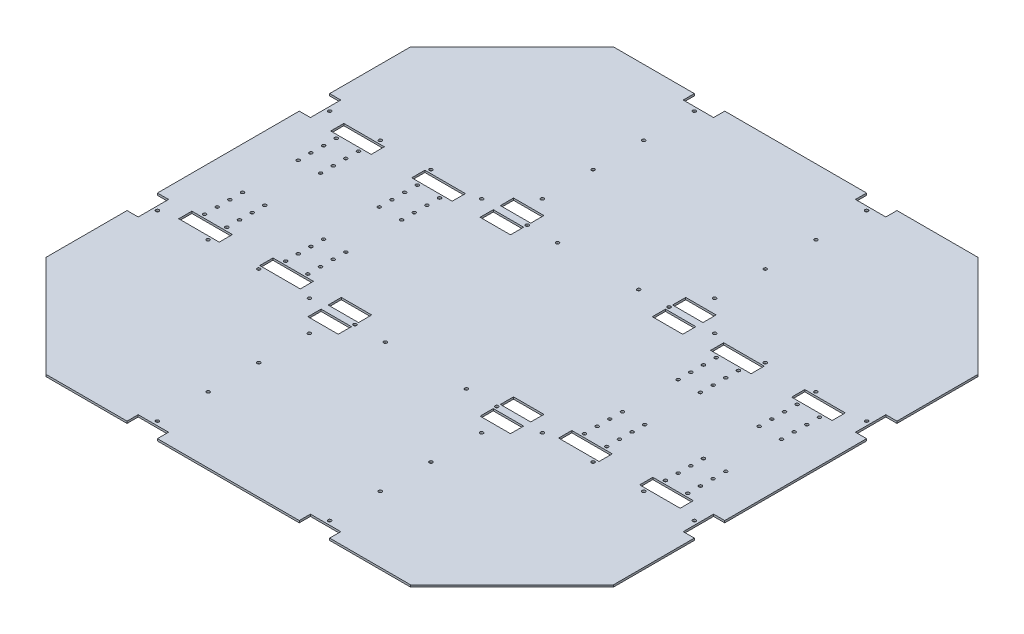
SolidWorks part; units mm, degrees
material "环氧树脂"
ref_plane "前视基准面" through (0, 0, 0) normal (0, 0, 1) x (1, 0, 0)
ref_plane "上视基准面" through (0, 0, 0) normal (0, 1, 0) x (1, 0, 0)
ref_plane "右视基准面" through (0, 0, 0) normal (1, 0, 0) x (0, 0, -1)
sketch "草图1" plane through (0, 0, 0) normal (0, 1, 0) x (1, 0, 0)
  line L0 (0, 365.534) -> (0, -389.8058) construction
  line L1 (-390.2913, 0) -> (444.6602, 0) construction
  line L3 (-280, 280) -> (280, 280)
  line L4 (-280, 280) -> (-280, -280)
  line L5 (-280, -280) -> (280, -280)
  line L6 (280, 280) -> (280, -280)
  line L7 (-280, 280) -> (280, -280) construction
  line L8 (-280, -280) -> (280, 280) construction
  point P5 (0, 0)
  point P10 (0, -389.8058)
  dimension "D1" = 560
extrude "凸台-拉伸1" add sketch "草图1" along normal blind 2
sketch "草图3" plane through (0, 2, 0) normal (0, 1, 0) x (1, 0, 0)
  line L0 (0, 280) -> (0, -280) construction
  line L1 (280, 280) -> (-280, 280) construction
  line L2 (-280, -280) -> (280, -280) construction
  circle A0 centre (265, 85) radius 1.6 construction
  circle A1 centre (265, 85) radius 1.6
  circle A2 centre (215, 85) radius 1.6 construction
  circle A3 centre (215, 85) radius 1.6
  circle A4 centre (165, 85) radius 1.6 construction
  circle A5 centre (165, 85) radius 1.6
  circle A6 centre (115, 85) radius 1.6 construction
  circle A7 centre (115, 85) radius 1.6
  circle A8 centre (85, 265) radius 1.6 construction
  circle A9 centre (85, 265) radius 1.6
  circle A10 centre (85, 215) radius 1.6 construction
  circle A11 centre (85, 215) radius 1.6
  circle A12 centre (85, 165) radius 1.6 construction
  circle A13 centre (85, 165) radius 1.6
  circle A14 centre (85, 115) radius 1.6 construction
  circle A15 centre (85, 115) radius 1.6
  circle A16 centre (-85, 265) radius 1.6 construction
  circle A17 centre (-85, 265) radius 1.6
  circle A18 centre (-85, 215) radius 1.6 construction
  circle A19 centre (-85, 215) radius 1.6
  circle A20 centre (-85, 165) radius 1.6 construction
  circle A21 centre (-85, 165) radius 1.6
  circle A22 centre (-85, 115) radius 1.6 construction
  circle A23 centre (-85, 115) radius 1.6
  circle A24 centre (-115, 85) radius 1.6 construction
  circle A25 centre (-115, 85) radius 1.6
  circle A26 centre (-165, 85) radius 1.6 construction
  circle A27 centre (-165, 85) radius 1.6
  circle A28 centre (-215, 85) radius 1.6 construction
  circle A29 centre (-215, 85) radius 1.6
  circle A30 centre (-265, 85) radius 1.6 construction
  circle A31 centre (-265, 85) radius 1.6
  circle A32 centre (70, 85) radius 1.6 construction
  circle A33 centre (70, 85) radius 1.6
  circle A34 centre (40, 85) radius 1.6 construction
  circle A35 centre (40, 85) radius 1.6
  circle A36 centre (-40, 85) radius 1.6 construction
  circle A37 centre (-40, 85) radius 1.6
  circle A38 centre (-70, 85) radius 1.6 construction
  circle A39 centre (-70, 85) radius 1.6
  circle A40 centre (70, -85) radius 1.6 construction
  circle A41 centre (70, -85) radius 1.6
  circle A42 centre (40, -85) radius 1.6 construction
  circle A43 centre (40, -85) radius 1.6
  circle A44 centre (-40, -85) radius 1.6 construction
  circle A45 centre (-40, -85) radius 1.6
  circle A46 centre (-70, -85) radius 1.6 construction
  circle A47 centre (-70, -85) radius 1.6
  circle A48 centre (-115, -85) radius 1.6 construction
  circle A49 centre (-115, -85) radius 1.6
  circle A50 centre (-165, -85) radius 1.6 construction
  circle A51 centre (-165, -85) radius 1.6
  circle A52 centre (-215, -85) radius 1.6 construction
  circle A53 centre (-215, -85) radius 1.6
  circle A54 centre (-265, -85) radius 1.6 construction
  circle A55 centre (-265, -85) radius 1.6
  circle A56 centre (115, -85) radius 1.6 construction
  circle A57 centre (115, -85) radius 1.6
  circle A58 centre (165, -85) radius 1.6 construction
  circle A59 centre (165, -85) radius 1.6
  circle A60 centre (215, -85) radius 1.6 construction
  circle A61 centre (215, -85) radius 1.6
  circle A62 centre (265, -85) radius 1.6 construction
  circle A63 centre (265, -85) radius 1.6
  circle A66 centre (85, -165) radius 1.6 construction
  circle A67 centre (85, -165) radius 1.6
  circle A68 centre (85, -215) radius 1.6 construction
  circle A69 centre (85, -215) radius 1.6
  circle A70 centre (85, -265) radius 1.6 construction
  circle A71 centre (85, -265) radius 1.6
  circle A72 centre (85, -115) radius 1.6 construction
  circle A73 centre (85, -115) radius 1.6
  circle A74 centre (-85, -115) radius 1.6 construction
  circle A75 centre (-85, -115) radius 1.6
  circle A76 centre (-85, -165) radius 1.6 construction
  circle A77 centre (-85, -165) radius 1.6
  circle A78 centre (-85, -215) radius 1.6 construction
  circle A79 centre (-85, -215) radius 1.6
  circle A80 centre (-85, -265) radius 1.6 construction
  circle A81 centre (-85, -265) radius 1.6
  circle A82 centre (136.5, 65) radius 1.6 construction
  circle A83 centre (136.5, 65) radius 1.6
  circle A84 centre (136.5, 52.5) radius 1.6 construction
  circle A85 centre (136.5, 52.5) radius 1.6
  circle A86 centre (136.5, 40) radius 1.6 construction
  circle A87 centre (136.5, 40) radius 1.6
  circle A88 centre (136.5, 27.5) radius 1.6 construction
  circle A89 centre (136.5, 27.5) radius 1.6
  circle A90 centre (136.5, -40) radius 1.6 construction
  circle A91 centre (136.5, -40) radius 1.6
  circle A92 centre (136.5, -27.5) radius 1.6 construction
  circle A93 centre (136.5, -27.5) radius 1.6
  circle A94 centre (136.5, -52.5) radius 1.6 construction
  circle A95 centre (136.5, -52.5) radius 1.6
  circle A96 centre (136.5, -65) radius 1.6 construction
  circle A97 centre (136.5, -65) radius 1.6
  circle A98 centre (158.5, -65) radius 1.6 construction
  circle A99 centre (158.5, -65) radius 1.6
  circle A100 centre (158.5, -52.5) radius 1.6 construction
  circle A101 centre (158.5, -52.5) radius 1.6
  circle A102 centre (158.5, -40) radius 1.6 construction
  circle A103 centre (158.5, -40) radius 1.6
  circle A104 centre (158.5, -27.5) radius 1.6 construction
  circle A105 centre (158.5, -27.5) radius 1.6
  circle A106 centre (158.5, 27.5) radius 1.6 construction
  circle A107 centre (158.5, 27.5) radius 1.6
  circle A108 centre (158.5, 40) radius 1.6 construction
  circle A109 centre (158.5, 40) radius 1.6
  circle A110 centre (158.5, 52.5) radius 1.6 construction
  circle A111 centre (158.5, 52.5) radius 1.6
  circle A112 centre (158.5, 65) radius 1.6 construction
  circle A113 centre (158.5, 65) radius 1.6
  circle A114 centre (216.5, 65) radius 1.6 construction
  circle A115 centre (216.5, 65) radius 1.6
  circle A116 centre (216.5, 52.5) radius 1.6 construction
  circle A117 centre (216.5, 52.5) radius 1.6
  circle A118 centre (216.5, 40) radius 1.6 construction
  circle A119 centre (216.5, 40) radius 1.6
  circle A120 centre (216.5, 27.5) radius 1.6 construction
  circle A121 centre (216.5, 27.5) radius 1.6
  circle A122 centre (216.5, -27.5) radius 1.6 construction
  circle A123 centre (216.5, -27.5) radius 1.6
  circle A124 centre (216.5, -40) radius 1.6 construction
  circle A125 centre (216.5, -40) radius 1.6
  circle A126 centre (216.5, -52.5) radius 1.6 construction
  circle A127 centre (216.5, -52.5) radius 1.6
  circle A128 centre (216.5, -65) radius 1.6 construction
  circle A129 centre (216.5, -65) radius 1.6
  circle A130 centre (238.5, -65) radius 1.6 construction
  circle A131 centre (238.5, -65) radius 1.6
  circle A132 centre (238.5, -52.5) radius 1.6 construction
  circle A133 centre (238.5, -52.5) radius 1.6
  circle A134 centre (238.5, -40) radius 1.6 construction
  circle A135 centre (238.5, -40) radius 1.6
  circle A136 centre (238.5, -27.5) radius 1.6 construction
  circle A137 centre (238.5, -27.5) radius 1.6
  circle A138 centre (238.5, 65) radius 1.6 construction
  circle A139 centre (238.5, 65) radius 1.6
  circle A140 centre (238.5, 52.5) radius 1.6 construction
  circle A141 centre (238.5, 52.5) radius 1.6
  circle A142 centre (238.5, 40) radius 1.6 construction
  circle A143 centre (238.5, 40) radius 1.6
  circle A144 centre (238.5, 27.5) radius 1.6 construction
  circle A145 centre (238.5, 27.5) radius 1.6
  circle A146 centre (-238.5, 27.5) radius 1.6
  circle A147 centre (-238.5, 40) radius 1.6
  circle A148 centre (-238.5, 52.5) radius 1.6
  circle A149 centre (-238.5, 65) radius 1.6
  circle A150 centre (-238.5, -27.5) radius 1.6
  circle A151 centre (-238.5, -40) radius 1.6
  circle A152 centre (-238.5, -52.5) radius 1.6
  circle A153 centre (-238.5, -65) radius 1.6
  circle A154 centre (-216.5, -65) radius 1.6
  circle A155 centre (-216.5, -52.5) radius 1.6
  circle A156 centre (-216.5, -40) radius 1.6
  circle A157 centre (-216.5, -27.5) radius 1.6
  circle A158 centre (-216.5, 27.5) radius 1.6
  circle A159 centre (-216.5, 40) radius 1.6
  circle A160 centre (-216.5, 52.5) radius 1.6
  circle A161 centre (-216.5, 65) radius 1.6
  circle A162 centre (-158.5, 65) radius 1.6
  circle A163 centre (-158.5, 52.5) radius 1.6
  circle A164 centre (-158.5, 40) radius 1.6
  circle A165 centre (-158.5, 27.5) radius 1.6
  circle A166 centre (-158.5, -27.5) radius 1.6
  circle A167 centre (-158.5, -40) radius 1.6
  circle A168 centre (-158.5, -52.5) radius 1.6
  circle A169 centre (-158.5, -65) radius 1.6
  circle A170 centre (-136.5, -65) radius 1.6
  circle A171 centre (-136.5, -52.5) radius 1.6
  circle A172 centre (-136.5, -27.5) radius 1.6
  circle A173 centre (-136.5, -40) radius 1.6
  circle A174 centre (-136.5, 27.5) radius 1.6
  circle A175 centre (-136.5, 40) radius 1.6
  circle A176 centre (-136.5, 52.5) radius 1.6
  circle A177 centre (-136.5, 65) radius 1.6
extrude "切除-拉伸1" cut sketch "草图3" against normal through all
chamfer "倒角1" distance 100 angle 45 4 edges at (280, 1, -280) (280, 1, 280) (-280, 1, 280) (-280, 1, -280)
sketch "草图4" plane through (0, 2, 0) normal (0, 1, 0) x (1, 0, 0)
  line L0 (0, 330.6962) -> (0, -354.5669) construction
  line L1 (-415.6081, 0) -> (451.2403, 0) construction
  line L2 (0, 0) -> (-230, 230) construction
  line L3 (-180, 280) -> (-280, 180) construction
  line L4 (-85, 265) -> (-85, 280) construction
  line L5 (180, 280) -> (-180, 280) construction
  line L6 (-280, 100) -> (-280, 70)
  line L7 (-100, 269) -> (-70, 269)
  line L8 (-100, 269) -> (-100, 280)
  line L9 (-100, 280) -> (-70, 280)
  line L10 (-70, 269) -> (-70, 280)
  line L11 (-100, 269) -> (-70, 280) construction
  line L12 (-100, 280) -> (-70, 269) construction
  line L13 (-269, 70) -> (-280, 70)
  line L14 (-269, 100) -> (-269, 70)
  line L15 (-269, 100) -> (-280, 100)
  line L16 (-115, 85) -> (-70, 85) construction
  line L17 (-85, 116.6) -> (-85, 85) construction
  line L18 (-100, 81.5) -> (-70, 81.5)
  line L19 (-100, 101.5) -> (-70, 101.5)
  line L20 (-100, 101.5) -> (-100, 88.5)
  line L21 (-100, 88.5) -> (-70, 88.5)
  line L22 (-70, 101.5) -> (-70, 88.5)
  line L23 (-100, 101.5) -> (-70, 88.5) construction
  line L24 (-100, 88.5) -> (-70, 101.5) construction
  line L25 (-70, 68.5) -> (-70, 81.5)
  line L26 (-100, 68.5) -> (-70, 68.5)
  line L27 (-100, 68.5) -> (-100, 81.5)
  line L28 (-238.5, 65) -> (-216.5, 65) construction
  line L29 (-227.5, 65) -> (-227.5, 85) construction
  line L30 (-158.5, 65) -> (-136.5, 65) construction
  line L31 (-247.5, 81.5) -> (-207.5, 81.5)
  line L32 (-247.5, 81.5) -> (-247.5, 68.5)
  line L33 (-247.5, 68.5) -> (-207.5, 68.5)
  line L34 (-207.5, 81.5) -> (-207.5, 68.5)
  line L35 (-247.5, 81.5) -> (-207.5, 68.5) construction
  line L36 (-247.5, 68.5) -> (-207.5, 81.5) construction
  line L37 (-147.5, 65) -> (-147.5, 81.5) construction
  line L38 (100, 88.5) -> (70, 88.5)
  line L39 (-167.5, 81.5) -> (-127.5, 81.5)
  line L40 (-167.5, 81.5) -> (-167.5, 68.5)
  line L41 (-167.5, 68.5) -> (-127.5, 68.5)
  line L42 (-127.5, 81.5) -> (-127.5, 68.5)
  line L43 (-167.5, 81.5) -> (-127.5, 68.5) construction
  line L44 (-167.5, 68.5) -> (-127.5, 81.5) construction
  line L45 (70, 101.5) -> (70, 88.5)
  line L46 (100, 101.5) -> (70, 101.5)
  line L47 (100, 101.5) -> (100, 88.5)
  line L48 (100, 68.5) -> (100, 81.5)
  line L49 (100, 68.5) -> (70, 68.5)
  line L50 (70, 68.5) -> (70, 81.5)
  line L51 (100, 81.5) -> (70, 81.5)
  line L52 (167.5, 68.5) -> (127.5, 68.5)
  line L53 (127.5, 81.5) -> (127.5, 68.5)
  line L54 (167.5, 81.5) -> (127.5, 81.5)
  line L55 (167.5, 81.5) -> (167.5, 68.5)
  line L56 (247.5, 68.5) -> (207.5, 68.5)
  line L57 (207.5, 81.5) -> (207.5, 68.5)
  line L58 (247.5, 81.5) -> (207.5, 81.5)
  line L59 (247.5, 81.5) -> (247.5, 68.5)
  line L60 (269, 100) -> (280, 100)
  line L61 (269, 100) -> (269, 70)
  line L62 (269, 70) -> (280, 70)
  line L63 (280, 100) -> (280, 70)
  line L64 (100, 280) -> (70, 280)
  line L65 (70, 269) -> (70, 280)
  line L66 (100, 269) -> (70, 269)
  line L67 (100, 269) -> (100, 280)
  line L68 (100, -269) -> (100, -280)
  line L69 (100, -269) -> (70, -269)
  line L70 (70, -269) -> (70, -280)
  line L71 (100, -280) -> (70, -280)
  line L72 (280, -100) -> (280, -70)
  line L73 (269, -70) -> (280, -70)
  line L74 (269, -100) -> (269, -70)
  line L75 (269, -100) -> (280, -100)
  line L76 (247.5, -81.5) -> (247.5, -68.5)
  line L77 (247.5, -81.5) -> (207.5, -81.5)
  line L78 (207.5, -81.5) -> (207.5, -68.5)
  line L79 (247.5, -68.5) -> (207.5, -68.5)
  line L80 (167.5, -81.5) -> (167.5, -68.5)
  line L81 (167.5, -81.5) -> (127.5, -81.5)
  line L82 (127.5, -81.5) -> (127.5, -68.5)
  line L83 (167.5, -68.5) -> (127.5, -68.5)
  line L84 (100, -81.5) -> (70, -81.5)
  line L85 (70, -68.5) -> (70, -81.5)
  line L86 (100, -68.5) -> (70, -68.5)
  line L87 (100, -68.5) -> (100, -81.5)
  line L88 (100, -101.5) -> (100, -88.5)
  line L89 (100, -101.5) -> (70, -101.5)
  line L90 (70, -101.5) -> (70, -88.5)
  line L91 (100, -88.5) -> (70, -88.5)
  line L92 (-100, -280) -> (-70, -280)
  line L93 (-70, -269) -> (-70, -280)
  line L94 (-100, -269) -> (-70, -269)
  line L95 (-100, -269) -> (-100, -280)
  line L96 (-100, -88.5) -> (-70, -88.5)
  line L97 (-70, -101.5) -> (-70, -88.5)
  line L98 (-100, -101.5) -> (-70, -101.5)
  line L99 (-100, -101.5) -> (-100, -88.5)
  line L100 (-100, -68.5) -> (-100, -81.5)
  line L101 (-100, -68.5) -> (-70, -68.5)
  line L102 (-70, -68.5) -> (-70, -81.5)
  line L103 (-100, -81.5) -> (-70, -81.5)
  line L104 (-167.5, -68.5) -> (-127.5, -68.5)
  line L105 (-127.5, -81.5) -> (-127.5, -68.5)
  line L106 (-167.5, -81.5) -> (-127.5, -81.5)
  line L107 (-167.5, -81.5) -> (-167.5, -68.5)
  line L108 (-247.5, -68.5) -> (-207.5, -68.5)
  line L109 (-207.5, -81.5) -> (-207.5, -68.5)
  line L110 (-247.5, -81.5) -> (-207.5, -81.5)
  line L111 (-247.5, -81.5) -> (-247.5, -68.5)
  line L112 (-269, -100) -> (-280, -100)
  line L113 (-269, -100) -> (-269, -70)
  line L114 (-269, -70) -> (-280, -70)
  line L115 (-280, -100) -> (-280, -70)
  circle A0 centre (-85, 115) radius 1.6 construction
  point P14 (-85, 274.5)
  point P33 (-85, 95)
  point P47 (-227.5, 75)
  point P58 (-147.5, 75)
  point P63 (0, 0)
  dimension "D1" = 4
  dimension "D2" = 30
  dimension "D3" = 30
  dimension "D4" = 13
  dimension "D5" = 10
  dimension "D6" = 10
  dimension "D7" = 40
  dimension "D8" = 13
extrude "切除-拉伸2" cut sketch "草图4" against normal through all contours L14 L15 L6 L13 | L115 L112 L113 L114 | L111 L110 L109 L108 | L107 L106 L105 L104 | L100 L103 L102 L101 | L99 L98 L97 L96 | L34 L31 L32 L33 | L42 L39 L40 L41 | L27 L26 L25 L18 | L48 L51 L50 L49 | L55 L54 L53 L52 | L59 L58 L57 L56 | L63 L60 L61 L62 | L74 L75 L72 L73 | L76 L79 L78 L77 | L80 L83 L82 L81 | L87 L86 L85 L84 | L88 L91 L90 L89 | L94 L95 L92 L93 | L71 L68 L69 L70 | L20 L21 L22 L19 | L8 L9 L10 L7 | L64 L65 L66 L67 | L38 L45 L46 L47
